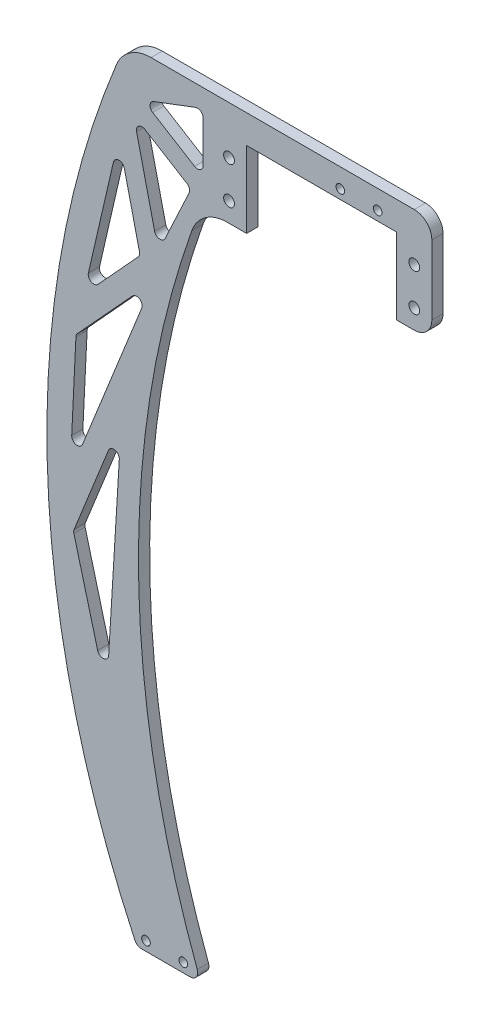
SolidWorks part; units mm, degrees
material "ABS"
ref_plane "Front" through (0, 0, 0) normal (0, 0, 1) x (1, 0, 0)
ref_plane "Top" through (0, 0, 0) normal (0, 1, 0) x (1, 0, 0)
ref_plane "Right" through (0, 0, 0) normal (1, 0, 0) x (0, 0, -1)
sketch "Esquisse1" plane through (0, 0, 0) normal (0, 0, 1) x (1, 0, 0)
  line L3 (-30.9, -14) -> (30.9, -14)
  line L4 (30.9, 14) -> (30.9, -14)
  line L5 (-30.9, -14) -> (30.9, 14) construction
  line L6 (30.9, -14) -> (0, 0) construction
  line L7 (-30.9, -194) -> (-48.1, -194) construction
  line L8 (-48.1, -194) -> (-30.9, -194)
  line L9 (30.9, 14) -> (-50.9, 14)
  arc A3 (-30.9, -14) -> (-30.9, -194) centre (202.3381, -104) ccw
  arc A5 (-50.9, 14) -> (-48.1, -194) centre (177.8162, -86.94) ccw
  point P0 (0, 0)
  dimension "D1" = 250
  dimension "D4" = 250
  dimension "D7" = 20
  dimension "D6" = 17.2
  dimension "D2" = 81.8
  dimension "D3" = 28
  dimension "D5" = 180
extrude "Boss.-Extru.1" add sketch "Esquisse1" along normal blind 3
sketch "Esquisse2" plane through (0, 0, 3) normal (0, 0, 1) x (1, 0, 0)
  line L0 (-30.9, 12.9) -> (-30.9, -14) construction
  line L1 (30.9, -14) -> (30.9, 14) construction
  line L2 (-30.9, -14) -> (30.9, -14) construction
  line L3 (-18.7, -14) -> (21.5, -14)
  line L4 (-18.7, -14) -> (-18.7, 6.4)
  line L5 (-18.7, 6.4) -> (21.5, 6.4)
  line L6 (21.5, -14) -> (21.5, 6.4)
  line L7 (-30.9, -14) -> (30.9, -14) construction
  dimension "D1" = 40.2
  dimension "D2" = 12.2
  dimension "D3" = 20.4
  dimension "D4" = 9.4
extrude "Enlèv. mat.-Extru.1" cut sketch "Esquisse2" against normal up to next
sketch "Esquisse3" plane through (0, 0, 3) normal (0, 0, 1) x (1, 0, 0)
  line L0 (21.5, -14) -> (21.5, 6.4) construction
  line L2 (21.5, -14) -> (30.9, -14) construction
  circle A2 centre (26.2, -8.8) radius 1.45
  circle A4 centre (-23.4, -8.8) radius 1.45
  circle A5 centre (-23.4, 1.2) radius 1.45
  circle A6 centre (26.2, 1.2) radius 1.45
  dimension "D1" = 2.9
  dimension "D2" = 4.7
  dimension "D3" = 5.2
  dimension "D4" = 2
  dimension "D5" = 2
extrude "Enlèv. mat.-Extru.2" cut sketch "Esquisse3" against normal up to next
fillet "Congé2" radius 4.7 2 edges at (30.9, -14, 1.5) (30.9, 14, 1.5)
fillet "Congé3" radius 10 2 edges at (-30.9, -14, 1.5) (-50.9, 14, 1.5)
fillet "Congé5" radius 2 2 edges at (-30.9, -194, 1.5) (-48.1, -194, 1.5)
sketch "Esquisse4" plane through (0, 0, 3) normal (0, 0, 1) x (1, 0, 0)
  line L0 (-33.5366, -11.101) -> (-42.3519, -30.0136)
  line L1 (-42.3519, -30.0136) -> (-48.9875, -1.6206)
  line L2 (-48.9875, -1.6206) -> (-33.5366, -11.101)
  line L3 (-52.9174, -8.973) -> (-47.2139, -33.3779)
  line L4 (-47.2139, -33.3779) -> (-62.3599, -49.9292)
  line L5 (-62.3599, -49.9292) -> (-52.9174, -8.973)
  line L6 (-43.7119, -37.698) -> (-64.3837, -60.2877)
  line L7 (-64.3837, -60.2877) -> (-65.9714, -93.1942)
  line L8 (-65.9714, -93.1942) -> (-43.7119, -37.698)
  line L9 (-46.4573, 3.0782) -> (-30.3519, -6.8037)
  line L10 (-30.3519, -6.8037) -> (-30.3519, 9.1554)
  line L11 (-30.3519, 9.1554) -> (-46.4573, 3.0782)
  line L12 (-52.2343, -74.1774) -> (-65.0874, -106.2221)
  line L13 (-65.0874, -106.2221) -> (-56.207, -139.6166)
  line L14 (-56.207, -139.6166) -> (-52.2343, -74.1774)
  dimension "D1" = 5.5
  dimension "D2" = 5.5
extrude "Enlèv. mat.-Extru.3" cut sketch "Esquisse4" against normal up to next
fillet "Congé6" radius 1.5 15 edges at (-65.9714, -93.1942, 1.5) (-64.3837, -60.2877, 1.5) (-43.7119, -37.698, 1.5) (-47.2139, -33.3779, 1.5) (-52.9174, -8.973, 1.5) (-62.3599, -49.9292, 1.5) (-42.3519, -30.0136, 1.5) (-33.5366, -11.101, 1.5) (-48.9875, -1.6206, 1.5) (-30.3519, 9.1554, 1.5) (-30.3519, -6.8037, 1.5) (-46.4573, 3.0782, 1.5) (-52.2343, -74.1774, 1.5) (-56.207, -139.6166, 1.5) (-65.0874, -106.2221, 1.5)
sketch "Esquisse5" plane through (0, 0, 3) normal (0, 0, 1) x (1, 0, 0)
  line L1 (21.5, 6.4) -> (-18.7, 6.4) construction
  line L2 (21.5, -14) -> (21.5, 6.4) construction
  circle A0 centre (16.4, 8.9) radius 1.15
  circle A1 centre (6.4, 8.9) radius 1.15
  dimension "D1" = 2.5
  dimension "D2" = 10
  dimension "D3" = 5.1
  dimension "D4" = 2.3
extrude "Enlèv. mat.-Extru.4" cut sketch "Esquisse5" against normal up to next
sketch "Esquisse6" plane through (0, 0, 3) normal (0, 0, 1) x (1, 0, 0)
  line L0 (-46.831, -194) -> (-33.7975, -194) construction
  circle A0 centre (-45.6427, -191.5) radius 1.15
  circle A1 centre (-35.6427, -191.5) radius 1.15
  dimension "D1" = 2.3
  dimension "D2" = 2.5
  dimension "D3" = 3
  dimension "D5" = 10
  dimension "D4" = 2
extrude "Enlèv. mat.-Extru.5" cut sketch "Esquisse6" against normal blind 10
